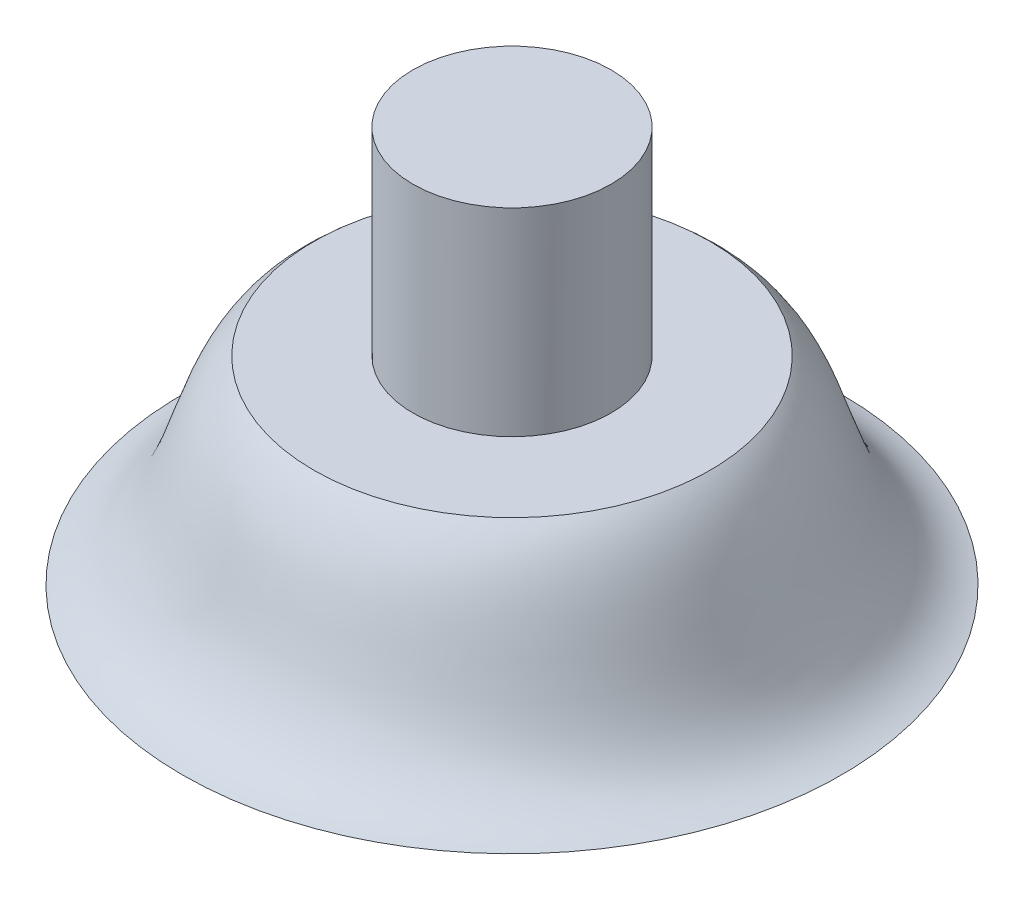
SolidWorks part; units mm, degrees
ref_plane "Plan de face" through (0, 0, 0) normal (0, 0, 1) x (1, 0, 0)
ref_plane "Plan de dessus" through (0, 0, 0) normal (0, 1, 0) x (1, 0, 0)
ref_plane "Plan de droite" through (0, 0, 0) normal (1, 0, 0) x (0, 0, -1)
sketch "Esquisse1" plane through (0, 0, 0) normal (0, 0, 1) x (1, 0, 0)
  line L0 (6.6285, 4.7013) -> (11.6285, 4.7013)
  line L1 (16.6285, 4.7013) -> (16.6285, -5.2987) construction
  line L2 (21.6285, 4.7013) -> (11.6285, 4.7013)
  line L3 (0, -5.2987) -> (33.2571, -5.2987)
  line L7 (26.6285, 4.7013) -> (21.6285, 4.7013)
  spline S0 degree 3 poles (0, -5.2987) (4.4714, -4.2306) (3.5804, 2.1866) (6.6285, 4.7013) knots 0 0 0 0 1 1 1 1
  spline S1 degree 3 poles (33.2571, -5.2987) (28.7856, -4.2306) (29.6767, 2.1866) (26.6285, 4.7013) knots 0 0 0 0 1 1 1 1
  dimension "D1" = 10
  dimension "D2" = 10
revolve "Révolution2" add sketch "Esquisse1" angle 360 about L1
sketch "Esquisse2" plane through (0, 4.7013, 0) normal (0, 1, 0) x (1, 0, 0)
  circle A0 centre (16.6285, 0) radius 5
  dimension "D1" = 10
extrude "Boss.-Extru.1" add sketch "Esquisse2" along normal blind 10
